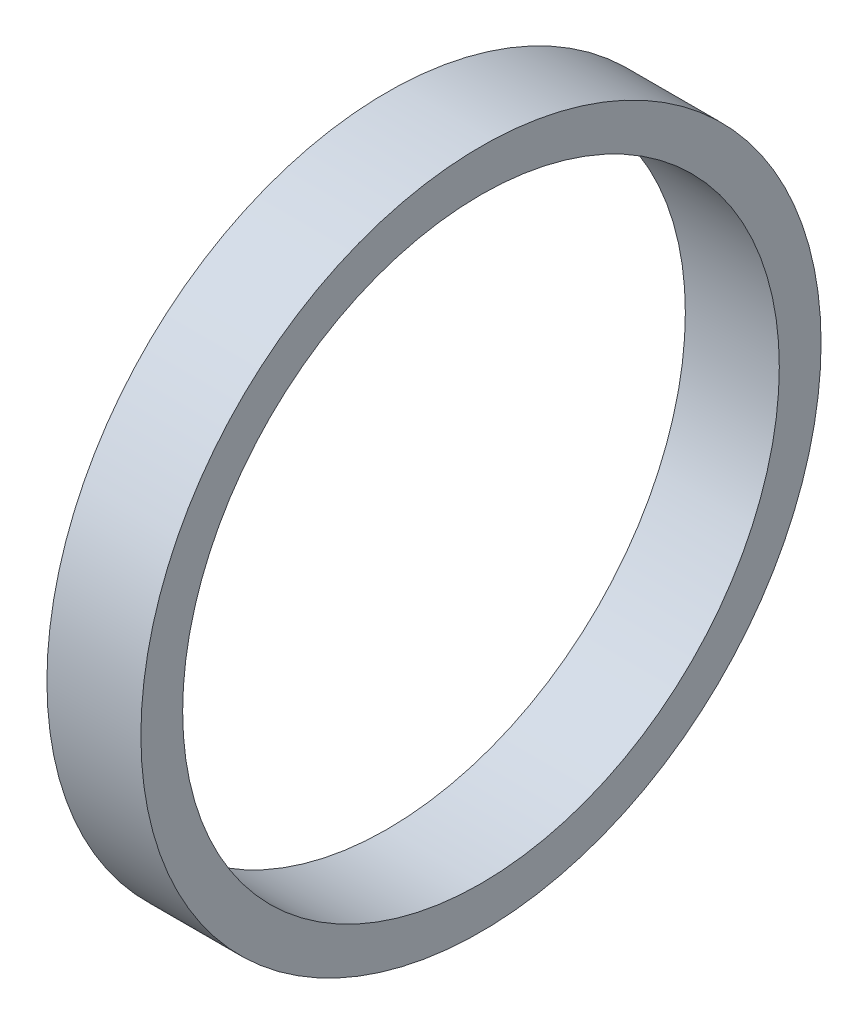
SolidWorks part; units mm, degrees
ref_plane "Front Plane" through (0, 0, 0) normal (0, 0, 1) x (1, 0, 0)
ref_plane "Top Plane" through (0, 0, 0) normal (0, 1, 0) x (1, 0, 0)
ref_plane "Right Plane" through (0, 0, 0) normal (1, 0, 0) x (0, 0, -1)
sketch "Sketch1" plane through (0, 0, 0) normal (1, 0, 0) x (0, 0, -1)
  circle A0 centre (0, 0) radius 3.175
  circle A1 centre (0, 0) radius 3.6195
  dimension "D1" = 6.35
  dimension "D2" = 7.239
extrude "Boss-Extrude1" add sketch "Sketch1" along normal blind 1
